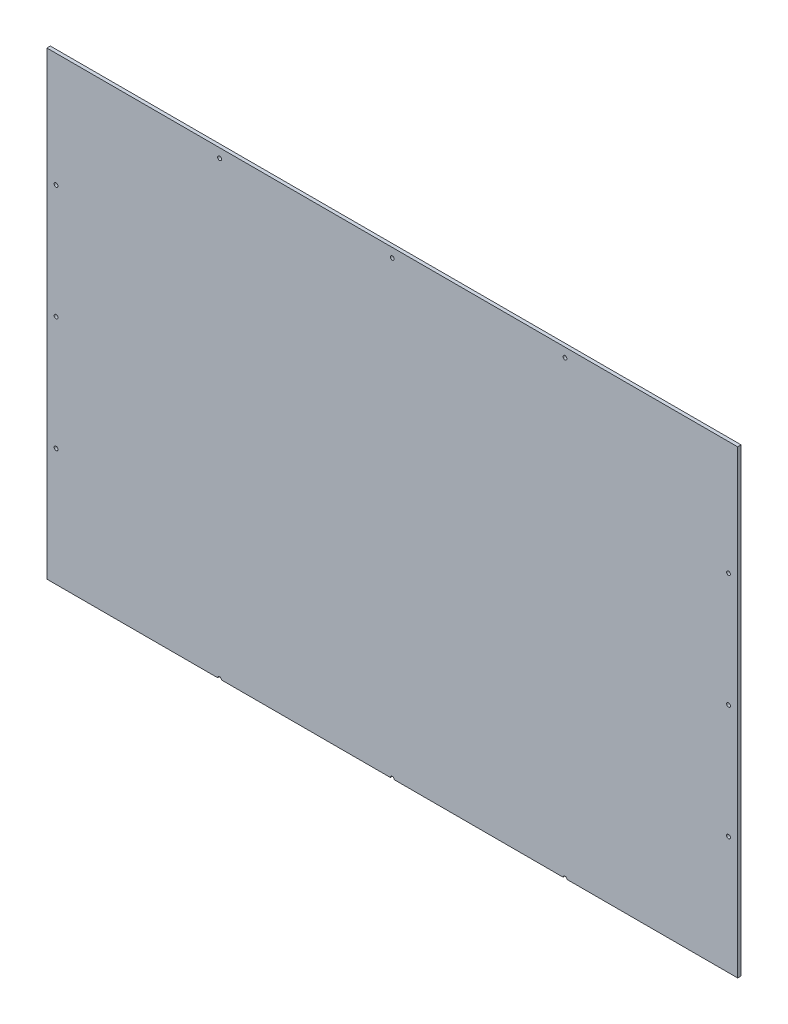
SolidWorks part; units mm, degrees
ref_plane "Front Plane" through (0, 0, 0) normal (0, 0, 1) x (1, 0, 0)
ref_plane "Top Plane" through (0, 0, 0) normal (0, 1, 0) x (1, 0, 0)
ref_plane "Right Plane" through (0, 0, 0) normal (1, 0, 0) x (0, 0, -1)
sketch "Sketch1" plane through (0, 0, 0) normal (0, 0, 1) x (1, 0, 0)
  line L1 (-452, 298.5) -> (452, 298.5)
  line L2 (-452, 298.5) -> (-452, -303.5)
  line L4 (452, 298.5) -> (452, -303.5)
  line L10 (-452, -303.5) -> (-228.5, -303.5)
  line L11 (2.5, -303.5) -> (223.5, -303.5)
  line L12 (228.5, -303.5) -> (452, -303.5)
  line L13 (-223.5, -303.5) -> (-2.5, -303.5)
  arc A5 (2.5, -303.5) -> (-2.5, -303.5) centre (0, -303.5) ccw
  arc A6 (228.5, -303.5) -> (223.5, -303.5) centre (226, -303.5) ccw
  arc A7 (-223.5, -303.5) -> (-228.5, -303.5) centre (-226, -303.5) ccw
  dimension "D3" = 2
  dimension "D1" = 602
  dimension "D2" = 904
  dimension "D4" = 452
extrude "Boss-Extrude1" add sketch "Sketch1" along normal blind 4.5 contours L1 L4 L12 A6 L11 A5 L13 A7 L10 L2
sketch "Sketch2" plane through (0, 0, 4.5) normal (0, 0, 1) x (1, 0, 0)
  line L0 (0, 298.5) -> (0, -296) construction
  line L1 (-452, 298.5) -> (452, 298.5) construction
  line L2 (-452, 298.5) -> (-452, -303.5) construction
  line L3 (452, 298.5) -> (452, -303.5) construction
  circle A1 centre (0, 286.5) radius 2.5
  circle A8 centre (440, -149.25) radius 2.5
  circle A9 centre (440, 0) radius 2.5
  circle A10 centre (440, 149.25) radius 2.5
  circle A13 centre (-440, -149.25) radius 2.5
  circle A14 centre (-440, 0) radius 2.5
  circle A15 centre (-440, 149.25) radius 2.5
  circle A16 centre (226, 286.5) radius 2.5
  circle A17 centre (-226, 286.5) radius 2.5
  dimension "D1" = 2
  dimension "D2" = 12
  dimension "D3" = 12
  dimension "D4" = 12
  dimension "D5" = 12
  dimension "D6" = 12
  dimension "D7" = 12
  dimension "D8" = 12
  dimension "D9" = 12
  dimension "D10" = 12
extrude "Cut-Extrude1" cut sketch "Sketch2" against normal blind 10
